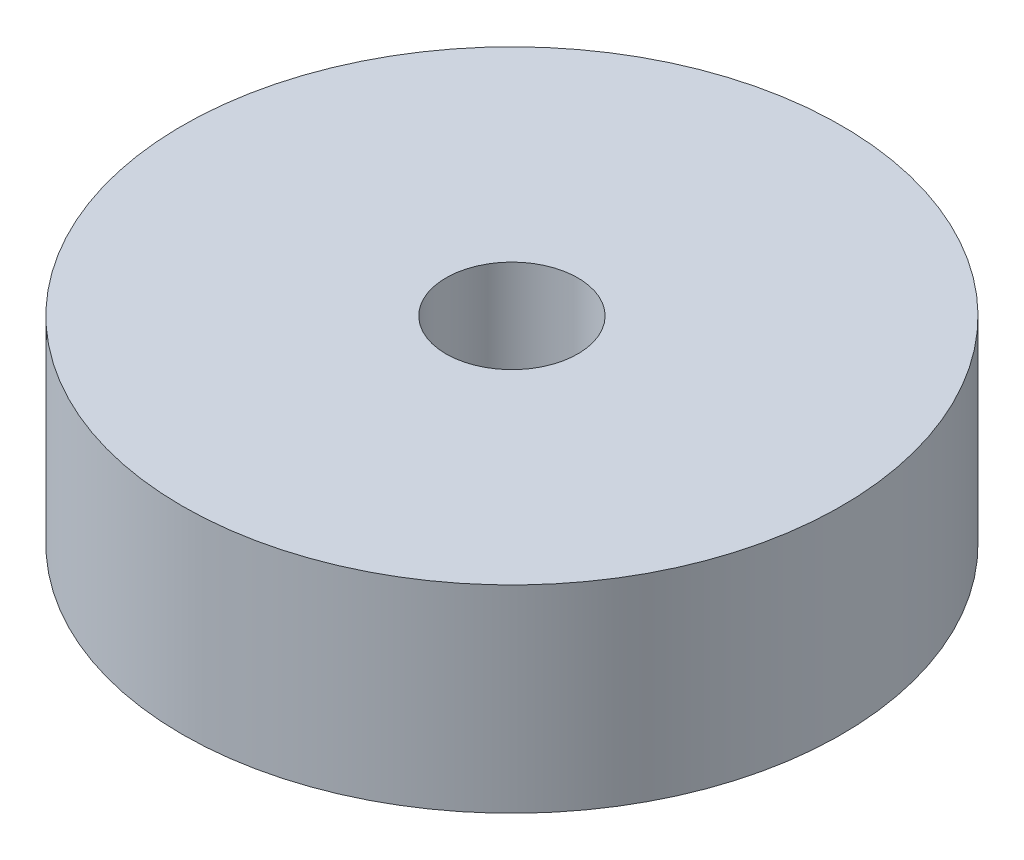
SolidWorks part; units mm, degrees
ref_plane "Front Plane" through (0, 0, 0) normal (0, 0, 1) x (1, 0, 0)
ref_plane "Top Plane" through (0, 0, 0) normal (0, 1, 0) x (1, 0, 0)
ref_plane "Right Plane" through (0, 0, 0) normal (1, 0, 0) x (0, 0, -1)
sketch "Sketch3" plane through (0, 0, 0) normal (0, 1, 0) x (1, 0, 0)
  circle A0 centre (0, 0) radius 15
  circle A1 centre (0, 0) radius 3
  dimension "D1" = 30
  dimension "D2" = 6
extrude "Boss-Extrude1" add sketch "Sketch3" along normal blind 9
